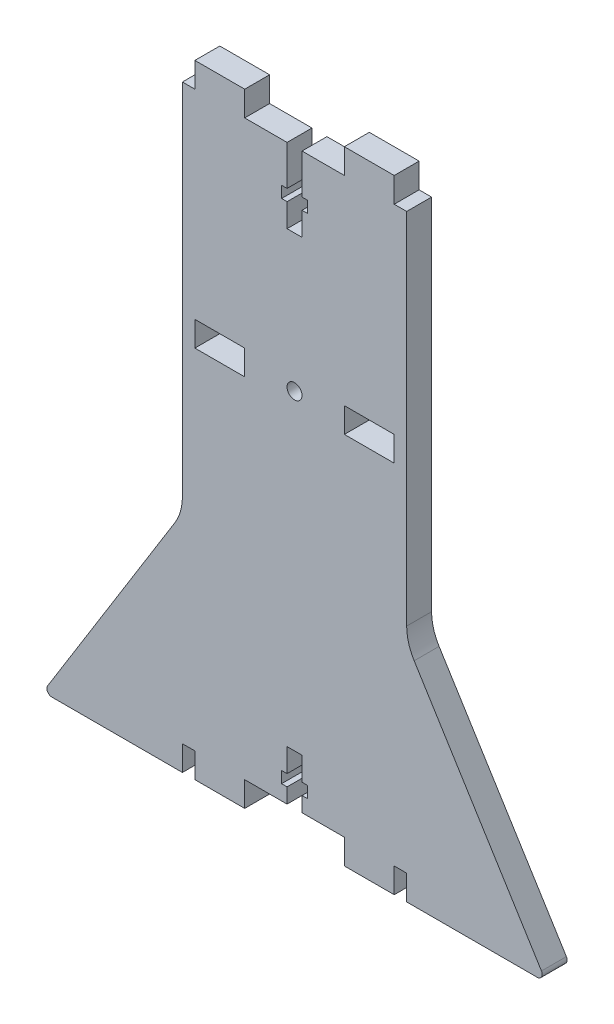
SolidWorks part; units mm, degrees
ref_plane "Front Plane" through (0, 0, 0) normal (0, 0, 1) x (1, 0, 0)
ref_plane "Top Plane" through (0, 0, 0) normal (0, 1, 0) x (1, 0, 0)
ref_plane "Right Plane" through (0, 0, 0) normal (1, 0, 0) x (0, 0, -1)
sketch "Sketch1" plane through (0, 0, 0) normal (0, 0, 1) x (1, 0, 0)
  line L1 (-32.5189, -56.1915) -> (-30.0189, -56.1915)
  line L2 (-30.0189, -56.1915) -> (-30.0189, -61.1915)
  line L3 (-30.0189, -61.1915) -> (-20.0189, -61.1915)
  line L4 (-20.0189, -61.1915) -> (-20.0189, -56.1915)
  line L6 (-0.0189, -56.1915) -> (-0.0189, -61.1915)
  line L7 (-0.0189, -61.1915) -> (9.9811, -61.1915)
  line L8 (9.9811, -61.1915) -> (9.9811, -56.1915)
  line L9 (9.9811, -56.1915) -> (12.4811, -56.1915)
  line L12 (-38.5749, -16.1038) -> (31.2699, -16.1038) construction
  line L13 (-11.5189, -56.1915) -> (-8.5189, -56.1915) construction
  line L14 (-8.5189, -56.1915) -> (-8.5189, -53.1915)
  line L15 (-8.5189, -50.8915) -> (-7.4189, -50.8915)
  line L16 (-12.6189, -53.1915) -> (-12.6189, -50.8915)
  line L17 (-7.4189, -53.1915) -> (-8.5189, -53.1915)
  line L18 (-8.5189, -50.8915) -> (-8.5189, -46.1915)
  line L19 (-8.5189, -46.1915) -> (-11.5189, -46.1915)
  line L20 (-11.5189, -46.1915) -> (-11.5189, -50.8915)
  line L21 (-11.5189, -53.1915) -> (-12.6189, -53.1915)
  line L22 (-7.4189, -50.8915) -> (-7.4189, -53.1915)
  line L23 (-12.6189, -50.8915) -> (-11.5189, -50.8915)
  line L24 (-11.5189, -53.1915) -> (-11.5189, -56.1915)
  line L25 (-10.0189, -46.1915) -> (-10.0189, -56.1915) construction
  line L26 (-11.5189, -56.1915) -> (-20.0189, -56.1915)
  line L27 (-8.5189, -56.1915) -> (-0.0189, -56.1915)
  line L28 (-10.0189, 43.8085) -> (-10.0189, 53.8085) construction
  line L29 (-11.5189, 58.8085) -> (-8.5189, 58.8085) construction
  line L30 (-10.0189, -57.0002) -> (-10.0189, 91.0448) construction
  line L31 (-8.5189, 58.8085) -> (-0.0189, 58.8085)
  line L32 (-11.5189, 58.8085) -> (-20.0189, 58.8085)
  line L33 (-11.5189, 50.8085) -> (-11.5189, 58.8085)
  line L34 (-12.6189, 48.5085) -> (-11.5189, 48.5085)
  line L35 (-7.4189, 48.5085) -> (-7.4189, 50.8085)
  line L36 (-11.5189, 50.8085) -> (-12.6189, 50.8085)
  line L37 (-11.5189, 43.8085) -> (-11.5189, 48.5085)
  line L38 (-8.5189, 43.8085) -> (-11.5189, 43.8085)
  line L39 (-8.5189, 48.5085) -> (-8.5189, 43.8085)
  line L40 (-7.4189, 50.8085) -> (-8.5189, 50.8085)
  line L41 (-12.6189, 50.8085) -> (-12.6189, 48.5085)
  line L42 (-8.5189, 48.5085) -> (-7.4189, 48.5085)
  line L43 (-8.5189, 58.8085) -> (-8.5189, 50.8085)
  line L44 (9.9811, 58.8085) -> (12.4811, 58.8085)
  line L45 (9.9811, 63.8085) -> (9.9811, 58.8085)
  line L46 (-0.0189, 63.8085) -> (9.9811, 63.8085)
  line L47 (-0.0189, 58.8085) -> (-0.0189, 63.8085)
  line L48 (-20.0189, 63.8085) -> (-20.0189, 58.8085)
  line L49 (-30.0189, 63.8085) -> (-20.0189, 63.8085)
  line L50 (-30.0189, 58.8085) -> (-30.0189, 63.8085)
  line L51 (-32.5189, 58.8085) -> (-30.0189, 58.8085)
  line L52 (-32.5189, -56.1915) -> (-32.5189, -61.1915)
  line L53 (-32.5189, -61.1915) -> (-60.5189, -61.1915)
  line L54 (-60.5189, -61.1915) -> (-32.5189, -16.1038)
  line L55 (-32.5189, 58.8085) -> (-32.5189, -16.1038)
  line L56 (12.4811, -56.1915) -> (12.4811, -61.1915)
  line L57 (12.4811, -61.1915) -> (40.4811, -61.1915)
  line L58 (40.4811, -61.1915) -> (12.4811, -16.1038)
  line L59 (12.4811, -16.1038) -> (12.4811, 58.8085)
  point P2 (-0.0189, -58.6915)
  point P57 (-10.0189, 43.8085)
  dimension "D1" = 10
  dimension "D2" = 10
  dimension "D3" = 5
  dimension "D4" = 20
  dimension "D5" = 28
  dimension "D6" = 2.5
  dimension "D7" = 5.2
  dimension "D8" = 3
  dimension "D9" = 2.3
  dimension "D10" = 3
  dimension "D11" = 10
  dimension "D12" = 5
  dimension "D13" = 28
  dimension "D14" = 2.5
  dimension "D15" = 3
  dimension "D16" = 3
  dimension "D17" = 5.2
  dimension "D18" = 45
  dimension "D19" = 10
  dimension "D20" = 20
  dimension "D21" = 22.5
  dimension "D22" = 2.5
  dimension "D23" = 5
  dimension "D24" = 5
  dimension "D25" = 5
  dimension "D26" = 2.5
  dimension "D27" = 10
  dimension "D28" = 53.0745
extrude "Boss-Extrude1" add sketch "Sketch1" along normal blind 5
sketch "Sketch2" plane through (0, 0, 5) normal (0, 0, 1) x (1, 0, 0)
  line L0 (-37.0155, 18.8085) -> (22.4174, 18.8085) construction
  line L2 (-30.0189, 18.8085) -> (-20.0189, 18.8085)
  line L3 (-30.0189, 18.8085) -> (-30.0189, 13.8085)
  line L4 (-30.0189, 13.8085) -> (-20.0189, 13.8085)
  line L5 (-20.0189, 18.8085) -> (-20.0189, 13.8085)
  line L6 (-0.0189, 18.8085) -> (9.9811, 18.8085)
  line L7 (-0.0189, 18.8085) -> (-0.0189, 13.8085)
  line L8 (-0.0189, 13.8085) -> (9.9811, 13.8085)
  line L9 (9.9811, 18.8085) -> (9.9811, 13.8085)
  line L14 (-30.0189, 58.8085) -> (-32.5189, 58.8085) construction
  line L15 (-35.7615, 16.3085) -> (19.4664, 16.3085) construction
  line L16 (-10.0189, 50.0273) -> (-10.0189, 1.4719) construction
  line L17 (-8.5189, 43.8085) -> (-11.5189, 43.8085) construction
  line L21 (-32.5189, 58.8085) -> (-32.5189, -16.1038) construction
  line L22 (12.4811, -16.1038) -> (12.4811, 58.8085) construction
  circle A0 centre (-10.0189, 16.3085) radius 1.5
  point P22 (9.9811, 16.3085)
  point P29 (-10.0189, 43.8085)
  dimension "D2" = 5
  dimension "D3" = 10
  dimension "D1" = 40
  dimension "D4" = 10
  dimension "D5" = 10
  dimension "D6" = 10
  dimension "D7" = 2.5
  dimension "D8" = 2.5
extrude "Cut-Extrude1" cut sketch "Sketch2" against normal blind 10
ref_plane "Plane4" through (12.4811, 58.8085, 5) normal (0, 1, 0) x (1, 0, 0)
fillet "Fillet1" radius 10 2 edges at (12.4811, -16.1038, 2.5) (-32.5189, -16.1038, 2.5)
fillet "Fillet2" radius 1 2 edges at (-60.5189, -61.1915, 2.5) (40.4811, -61.1915, 2.5)
